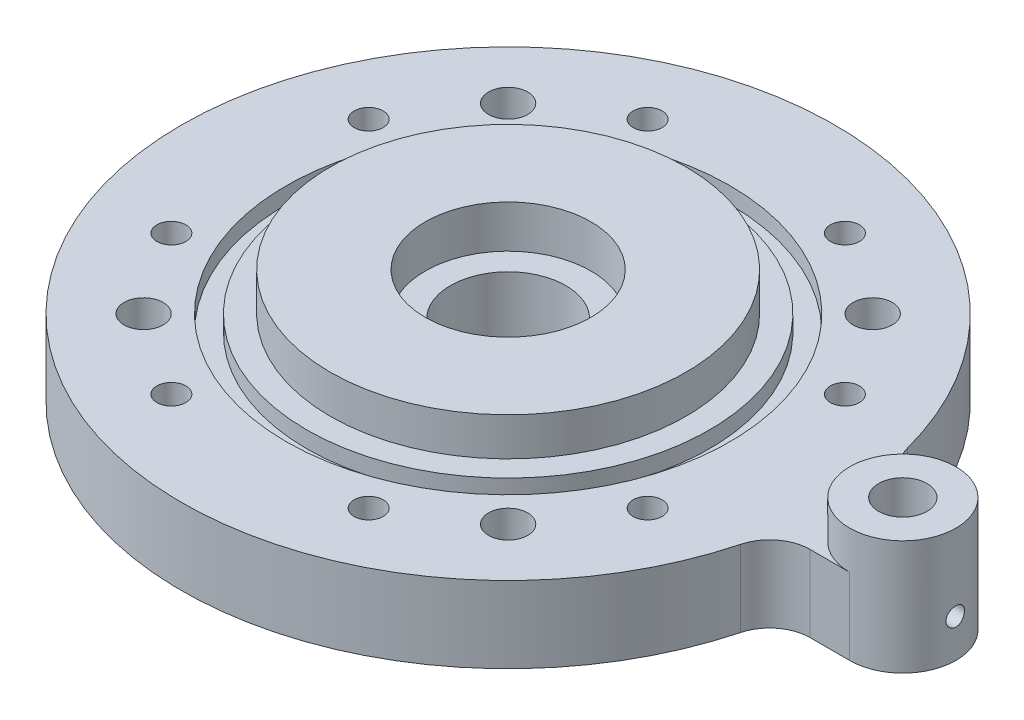
SolidWorks part; units mm, degrees
material "1060 Alloy"
ref_plane "Front" through (0, 0, 0) normal (0, 0, 1) x (1, 0, 0)
ref_plane "Top" through (0, 0, 0) normal (0, 1, 0) x (1, 0, 0)
ref_plane "Right" through (0, 0, 0) normal (1, 0, 0) x (0, 0, -1)
sketch "Sketch1" plane through (0, 0, 0) normal (0, 1, 0) x (1, 0, 0)
  line L0 (58.8962, 0) -> (68.0634, 0) construction
  line L1 (61.2588, 9.1672) -> (68.0634, 9.1672)
  line L2 (61.2588, -9.1672) -> (68.0634, -9.1672)
  line L3 (58.8962, 0) -> (77.2306, 0) construction
  line L4 (58.8962, 0) -> (56.3562, 0) construction
  arc A0 (54.4905, 14.3809) -> (54.4905, -14.3809) centre (0, 0) ccw
  circle A1 centre (0, 0) radius 56.3562 construction
  arc A2 (68.0634, -9.1672) -> (68.0634, 9.1672) centre (68.0634, 0) ccw
  arc A3 (54.4905, 14.3809) -> (61.2588, 9.1672) centre (61.2588, 16.1672) ccw
  arc A4 (61.2588, -9.1672) -> (54.4905, -14.3809) centre (61.2588, -16.1672) ccw
  point P5 (34.5422, 0)
  point P10 (55.6057, 9.1672)
  dimension "D1" = 112.7125
  dimension "D4" = 7
  dimension "D2" = 18.3344
  dimension "D3" = 18.3344
  dimension "D5" = 2.54
extrude "base" add sketch "Sketch1" along normal blind 13.175
sketch "Sketch2" plane through (0, 13.175, 0) normal (0, 1, 0) x (1, 0, 0)
  line L0 (68.0634, 9.1672) -> (68.0634, -9.1672) construction
  circle A0 centre (0, 0) radius 30.6705
  arc A1 (68.0634, -9.1672) -> (68.0634, 9.1672) centre (68.0634, 0) ccw construction
  circle A2 centre (68.0634, 0) radius 9.1672
  circle A3 centre (68.0634, 0) radius 4.1672
  dimension "D1" = 61.341
  dimension "D2" = 8.3344
sketch "Sketch3" plane through (0, 0, 0) normal (0, -1, 0) x (1, 0, 0)
  line L0 (0, 0) -> (77.2306, 0) construction
  line L1 (0, 0) -> (39.8499, -39.8499) construction
  circle A0 centre (0, 0) radius 44.45 construction
  circle A1 centre (-31.4309, -31.4309) radius 3.3734
  circle A2 centre (-31.4309, 31.4309) radius 3.3734
  circle A3 centre (31.4309, 31.4309) radius 3.3734
  circle A4 centre (31.4309, -31.4309) radius 3.3734
  arc A5 (68.0634, -9.1672) -> (68.0634, 9.1672) centre (68.0634, 0) ccw construction
  arc A6 (54.4905, 14.3809) -> (54.4905, -14.3809) centre (0, 0) ccw construction
  point P14 (0, 0)
  dimension "D1" = 88.9
  dimension "D2" = 6.7469
  dimension "D4" = 45
  dimension "D3" = 4
extrude "square bolt holes" cut sketch "Sketch3" against normal through all
sketch "Sketch4" plane through (0, 13.175, 0) normal (0, 1, 0) x (1, 0, 0)
  line L0 (0, 0) -> (0, 44.45) construction
  line L1 (0, 44.45) -> (0, 0) construction
  line L2 (0, 0) -> (17.0103, 41.0664) construction
  circle A0 centre (0, 0) radius 44.45 construction
  circle A1 centre (17.0103, 41.0664) radius 2.5
  dimension "D1" = 88.9
  dimension "D3" = 5
  dimension "D2" = 22.5
extrude "housing bolts" cut sketch "Sketch4" against normal blind 44.33
pattern_circular "CirPattern1" count 8 over 360 about axis through (0, 0, 0) along (0, 1, 0) of "housing bolts"
extrude "impeller cavity riser" add sketch "Sketch2" along normal blind 6.59
sketch "Sketch5" plane through (0, 19.765, 0) normal (0, 1, 0) x (1, 0, 0)
  circle A0 centre (0, 0) radius 14.2875
  dimension "D1" = 28.575
extrude "seal bore" cut sketch "Sketch5" against normal blind 7.35
sketch "Sketch6" plane through (0, 12.415, 0) normal (0, 1, 0) x (1, 0, 0)
  circle A0 centre (0, 0) radius 9.9375
  dimension "D1" = 19.875
extrude "bore" cut sketch "Sketch6" against normal blind 39.3
sketch "pressure tap plane alignment" plane through (0, 0, 0) normal (0, -1, 0) x (1, 0, 0)
  line L1 (0, 0) -> (56.3562, 0) construction
  line L2 (56.3562, 0) -> (56.3562, 56.3563) construction
  line L3 (56.3562, 56.3563) -> (0, 56.3562) construction
  circle A0 centre (0, 0) radius 56.3562 construction
  circle A1 centre (0, 0) radius 56.3562 construction
ref_plane "pressure tap plane" through (56.3562, 0, 0) normal (1, 0, 0) x (0, 0, -1)
sketch "Sketch9" plane through (56.3562, 0, 0) normal (1, 0, 0) x (0, 0, -1)
  line L0 (0, 0) -> (0, 13.175) construction
  line L1 (56.3562, 13.175) -> (-56.3563, 13.175) construction
  circle A0 centre (0, 6.5875) radius 1.5875
  dimension "D1" = 3.175
extrude "pressure tap" cut sketch "Sketch9" against normal blind 56.3562 and the other way through all
sketch "Sketch10" plane through (0, 13.175, 0) normal (0, 1, 0) x (1, 0, 0)
  circle A0 centre (68.0634, 0) radius 1.5875
  dimension "D1" = 3.175
extrude "pressure tap vertical hole" cut sketch "Sketch10" against normal blind 8.175
sketch "Sketch12" plane through (0, 13.175, 0) normal (0, 1, 0) x (1, 0, 0)
  circle A0 centre (0, 0) radius 34.7218
  circle A1 centre (0, 0) radius 38.2524
  dimension "D1" = 76.5048
  dimension "D2" = 69.4436
extrude "o ring feature" cut sketch "Sketch12" against normal blind 2.8245
equation "\"de\" = 0.43in\t\t\t'entrance eye diameter"
equation "\"d2\" = 2.1in \t\t\t'outer diameter of the impeller"
equation "\"d_exit\" = 0.18in \t\t'throat aka d1"
equation "\"theta\" = 12\t\t\t'angle of blades from inner to outer "
equation "\"impeller upper clearance\"= .5mm"
equation "\"impeller horizontal clearance\"= (\"d2\"*1.15 - \"d2\")/2 \t\t'clearance based on D2-D3 ratio for circular volute, ranges 1.15 to 1.2"
equation "\"impeller bottom clearance\"= .5mm"
equation "\"impeller base thickness\"= 2mm"
equation "\"impeller dowel diameter\" = 2mm"
equation "\"impeller bolt head diameter\" = \"m4 head bore diameter\""
equation "\"impeller bolt head depth\" = 4mm"
equation "\"impeller bolt stop depth\" = 3mm"
equation "\"impeller bolt bore\" = \"m4 clearance\""
equation "\"impeller shaft bore depth\" = 12mm"
equation "\"impeller shaft bore\" = 8mm"
equation "\"impeller boss depth\" = \"impeller shaft bore depth\"+\"impeller bolt stop depth\"+\"impeller bolt head depth\"-\"impeller base thickness\""
equation "\"impeller boss diameter\" = \"upper seal ID\""
equation "\"impeller dowel length\" = 2mm*2 + \"impeller shaft bore\""
equation "\"coupler motor shaft hole ID\"= 8mm"
equation "\"coupler OD\"= 17mm"
equation "\"coupler length\"= 25mm"
equation "\"motor OD\" = 64mm"
equation "\"motor shaft diameter\"= 8mm"
equation "\"motor shaft pride\"= 32mm"
equation "\"motor to bearing plate distance\" = \"motor shaft pride\" + 2mm +\"coupler length\"/2"
equation "\"square plate bolt bore\" = \"m8 clearance\""
equation "\"square plate bolt head diameter\" = 13.5mm"
equation "\"square plate bolt pattern diameter\"= 3.5in"
equation "\"motor mount center bore\"= \"coupler OD\"+ 4mm"
equation "\"motor mount post radius\"= ( 3 * \"square plate bolt bore\" ) / 2"
equation "\"motor mount m4 screw hole diameter\"= 4mm"
equation "\"motor mount m4 head diameter\"= 7.25mm"
equation "\"motor mount m4 head depth\"= 4mm"
equation "\"motor mount m4 pattern diamater\" = 30mm"
equation "\"motor mount plate thickness\"= 8mm + \"motor mount m4 head depth\""
equation "\"shaft coupler section diameter\" = 8mm"
equation "\"shaft coupler section length\" = \"motor to bearing plate distance\" - \"motor shaft pride\" - 2mm"
equation "\"shaft bearing section diameter\" = \"bearing ID\""
equation "\"shaft bearing section length\" = \"bearing plate stop depth\" + \"bearing depth\""
equation "\"shaft bearing stop diameter\" = \"bearing ID\" + 4mm"
equation "\"shaft bearing stop length\" = 3mm"
equation "\"impeller cavity center height\"= \"impeller bottom clearance\" + \"impeller upper clearance\" + \"impeller center height\""
equation "\"impeller cavity diameter\"= 2 * \"impeller horizontal clearance\" + \"d2\" \t\t\t\t\t\t\t\t\t'called D3 analytically"
equation "\"impeller cavity outer height\"= \"impeller bottom clearance\" + \"impeller upper clearance\" + \"impeller base thickness\" + \"b2\" \t\t'this is height at impeller diameter d2, not at d3"
equation "\"impeller housing thickness\"= \"impeller housing exit threaded diameter\" + 2*\"impeller housing outlet grip\""
equation "\"impeller housing diameter\" = \"square plate bolt pattern diameter\" + 2*\"motor mount post radius\""
equation "\"impeller housing bolt count\" = 8"
equation "\"impeller housing bolt diameter\" = \"m6 clearance\""
equation "\"impeller housing bolt pattern diameter\" = 3.5in"
equation "\"impeller housing threaded inlet diameter\" = 0.71875in \t'this is the 23/32 drill size for 1/2 NPT fitting https://www.mcmaster.com/#50715k269/=176pljy"
equation "\"impeller housing threaded inlet depth\"= .6in"
equation "\"impeller housing exit threaded diameter\"= 0.515625in \t\t'this is the 33/64 drill size for 9/16-18 fitting, expecting swagelok SS-8FK0-1-6STH fitting"
equation "\"impeller housing exit threaded depth\"= 10mm"
equation "\"impeller housing diffuser conical angle\"=10"
equation "\"impeller housing diffuser tangent angle\"=5"
equation "\"impeller housing outlet grip\" = 5mm"
equation "\"D1@Sketch1\"=\"impeller housing diameter\""
equation "\"D1@base\" = \"upper seal plate thickness\""
equation "\"D1@Sketch2\"=\"impeller cavity diameter\""
equation "\"D1@Sketch3\"=\"square plate bolt pattern diameter\""
equation "\"D2@Sketch3\"=\"m8 tap\""
equation "\"D1\"= \"upper seal plate thickness\" - 2mm"
equation "\"D1@Sketch4\"=\"impeller housing bolt pattern diameter\""
equation "\"D2@Sketch4\"=360/\"impeller housing bolt count\"/2"
equation "\"D3@Sketch4\"=\"m6 tap\""
equation "\"D1@CirPattern1\"=\"impeller housing bolt count\""
equation "\"D1@impeller cavity riser\" = \"upper seal plate riser\""
equation "\"D1@Sketch5\" = \"upper seal OD\""
equation "\"D1@seal bore\" = \"upper seal bore\""
equation "\"D1@Sketch6\" = \"upper seal ID\" + 4mm"
equation "\"D1@Sketch9\" = \"upper seal plate pressure hole diameter\""
equation "\"D1@pressure tap\"=\"impeller housing diameter\"/2"
equation "\"de_length\" = 10mm\t\t'entrance eye consistent length"
equation "\"square plate bolt head depth\" = 8mm"
equation "\"shaft impeller section diameter\" = \"impeller shaft bore\""
equation "\"shaft impeller section length\" = \"upper seal plate thickness\" + \"upper seal plate riser\" + \"impeller bottom clearance\" + \"impeller base thickness\" - \"impeller bolt head depth\" - \"impeller bolt stop depth\""
equation "\"impeller housing diffuser final diameter\" = .38in\t\t'aka d2'"
equation "\"D2@Sketch1\" = \"upper seal plate pressure tap diameter\" + \"upper seal plate pressure tap grip\" * 2"
equation "\"D3@Sketch1\" = \"upper seal plate pressure tap diameter\" + \"upper seal plate pressure tap grip\" * 2"
equation "\"D2@pressure tap\"=\"big seal plate pressure tap diameter\"/2+\"big seal plate pressure tap grip\""
equation "\"D2@Sketch2\" = \"upper seal plate pressure tap diameter\""
equation "\"D1@Sketch10\" = \"upper seal plate pressure hole diameter\""
equation "\"D1@pressure tap vertical hole\"= \"upper seal plate thickness\" / 2 + \"upper seal plate pressure hole diameter\" / 2"
equation "\"end mill size\" = 0.375in\t'for 3/8 endmill"
equation "\"m6 clearance\" = 0.234375in\t'this is 15/64 bit = 5.95mm, could use 6mm bit, B bit for 6.04mm or 1/4 bit for 6.35mm"
equation "\"m6 tap\" = 5mm\t\t\t'5mm is appropriate, could use 13/64 or #5,6,7"
equation "\"m6 head bore diameter\" = 11mm\t\t"
equation "\"m6 head bore depth\" = 7mm\t'actual is 6mm"
equation "\"m8 clearance\" = 0.3125in\t'this is 5/16in for 7.93mm, could use 8mm, O,P, or 21/64"
equation "\"m8 tap\" = 0.265625in\t\t'this is 17/64 for 6.746875mm"
equation "\"m8 head bore diameter\" = 14mm"
equation "\"m8 head bore depth\" = 9mm\t'actual is 8mm"
equation "\"ce\" = 3.14*\"de\"\t\t'entrance eye circumference"
equation "\"s_open\" = \"av\"/\"b1\"\t\t'width of open area"
equation "\"impeller center height\" = \"impeller base thickness\" + \"b1\"\t'impeller height at de"
equation "\"impeller outer height\" = \"impeller base thickness\" + \"b2\"\t'impeller height at de"
equation "\"lower seal OD\" = .917in\t\t'this is https://www.mcmaster.com/#9281k121/=174001b"
equation "\"lower seal ID\"= .375in"
equation "\"lower seal depth\" = .625in + .218in"
equation "\"lower seal bore\" = \"lower seal depth\" + 1mm"
equation "\"upper seal OD\" = 1.125in\t'this is https://www.mcmaster.com/#5154t33/=173zuau, needs to be visually inspected before machining!"
equation "\"upper seal ID\"= 0.625in"
equation "\"upper seal depth\"= .25in\t'aka height; these values need to be confirmed by inspection!! We may want to compress the height."
equation "\"upper seal bore\" = \"upper seal depth\" + 1mm"
equation "\"lower seal plate lip depth\" = 2mm"
equation "\"lower seal plate lip ID\" = \"lower seal OD\" - 3mm"
equation "\"lower seal plate thickness\" = \"lower seal plate lip depth\" + \"lower seal bore\""
equation "\"shaft lower seal section diameter\" = \"lower seal ID\""
equation "\"shaft lower seal section length\" = \"lower seal plate thickness\" + 1mm"
equation "\"upper seal plate thickness\" = \"upper seal plate pressure hole diameter\"+10mm"
equation "\"upper seal plate lip ID\" = \"upper seal OD\" - 3mm"
equation "\"upper seal plate riser\" = 6.59mm \t\t'this number needs to be read from the housing file"
equation "\"upper seal plate pressure hole diameter\" = .125in\t'this is 1/8 drill "
equation "\"upper seal plate pressure tap diameter\" = .328125in \t'this is 21/64 drill for a 1/8 ANPT tap"
equation "\"upper seal plate pressure tap grip\" = 5mm\t\t'this is the area around the tap so it doesn't crack"
equation "\"upper seal plate pressure tap depth\" = 12mm"
equation "\"bearing OD\" = 30mm"
equation "\"bearing ID\"= 10mm"
equation "\"bearing depth\"= 9mm"
equation "\"bearing outer race thickness\"= 1mm"
equation "\"bearing inner race thickness\"= 1mm"
equation "\"bearing bore\" = \"bearing depth\" + 1mm"
equation "\"z\" = 8\t\t\t\t'number of blades"
equation "\"b2\" = .2in\t\t\t'tip height from disc surface at d2; slightly higher than d_exit"
equation "\"b1\" = \"b2\" + (\"d2\"/2 - \"de\"/2)*tan(\"theta\") \t\t\t'tip height from disc surface at inlet eye"
equation "\"ae\" = 3.14*(\"de\"^2)/4\t\t'entrance eye area'"
equation "\"av_ratio\" = .325\t\t'ratio of av/ae at N_s of 470, range is .275 to .375, .325 ideal. High ratio means bigger area means smaller blades"
equation "\"av\" = \"ae\"*\"av_ratio\"\t\t'area between just two blades"
equation "\"s\"=\"ce\" - \"z\"*\"s_open\""
equation "\"bearing plate stop ID\" = \"bearing OD\" - 4mm"
equation "\"bearing plate stop depth\" = 3mm"
equation "\"bearing plate thickness\" = \"bearing bore\" + \"bearing plate stop depth\" + \"shaft bearing stop length\""
equation "\"m4 clearance\" = 0.171875in \t'this is 11/64 bit for 4.36mm"
equation "\"m4 tap\" = 0.125in\t\t'this is 1/8 bit for 3.17mm"
equation "\"m4 head bore diameter\" = 7.5mm"
equation "\"m4 head bore depth\" = 5mm\t'actual is ~4mm"
equation "\"big o-ring thickness\" = .139in"
equation "\"big o-ring OD\" = 2.734in"
equation "\"big o-ring ID\" = 3.012in"
equation "\"big o-ring groove depth\" = \"big o-ring thickness\"*4/5"
equation "\"D1@Sketch12\"=\"big o-ring ID\""
equation "\"D2@Sketch12\"=\"big o-ring OD\""
equation "\"D1@o ring feature\" = \"big o-ring groove depth\""
equation "\"min blade thickness\" = .15in"
equation "\"diffuser cartridge OD\" =.75in"
equation "\"diffuser flange bolt pattern diameter\" = 1.4in"
